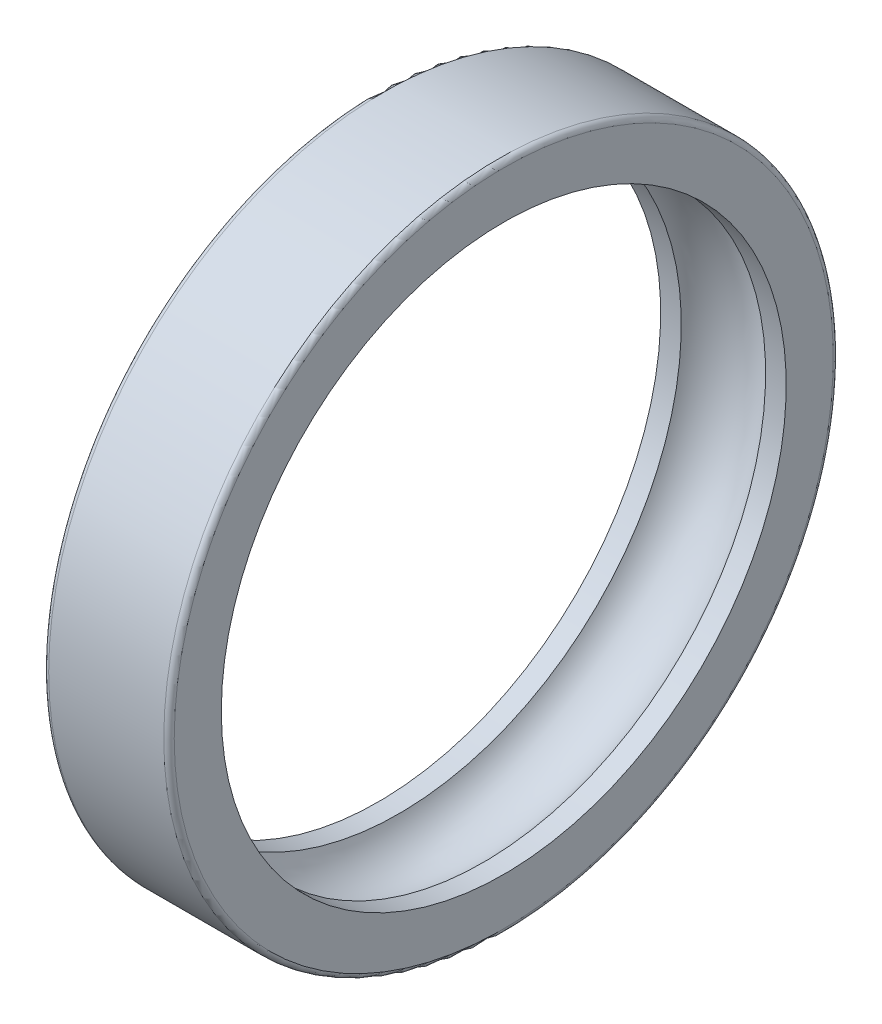
SolidWorks part; units mm, degrees
ref_plane "Front Plane" through (0, 0, 0) normal (0, 0, 1) x (1, 0, 0)
ref_plane "Top Plane" through (0, 0, 0) normal (0, 1, 0) x (1, 0, 0)
ref_plane "Right Plane" through (0, 0, 0) normal (1, 0, 0) x (0, 0, -1)
sketch "Sketch2" plane through (0, 0, 0) normal (0, 0, 1) x (1, 0, 0)
  line L0 (-83.864, 0) -> (208.477, 0) construction
  line L1 (0, 0) -> (0, 256.6712) construction
  line L2 (40.3113, 270) -> (60, 270)
  line L3 (-60, 270) -> (-40.3113, 270)
  line L4 (-60, 270) -> (-60, 320)
  line L5 (-60, 320) -> (60, 320)
  line L6 (60, 270) -> (60, 320)
  line L7 (-60, 270) -> (60, 320) construction
  line L8 (-60, 320) -> (60, 270) construction
  arc A0 (40.3113, 270) -> (-40.3113, 270) centre (0, 250) ccw
  point P7 (0, 295)
  dimension "D2" = 90
  dimension "D1" = 250
  dimension "D3" = 50
  dimension "D4" = 120
revolve "Revolve1" add sketch "Sketch2" angle 360 about L0
fillet "Fillet1" radius 5 2 edges at (60, 0, 320) (-60, 0, 320)
scale "Scale1" scale about centroid uniform scaling yes scale factor 0.277778
